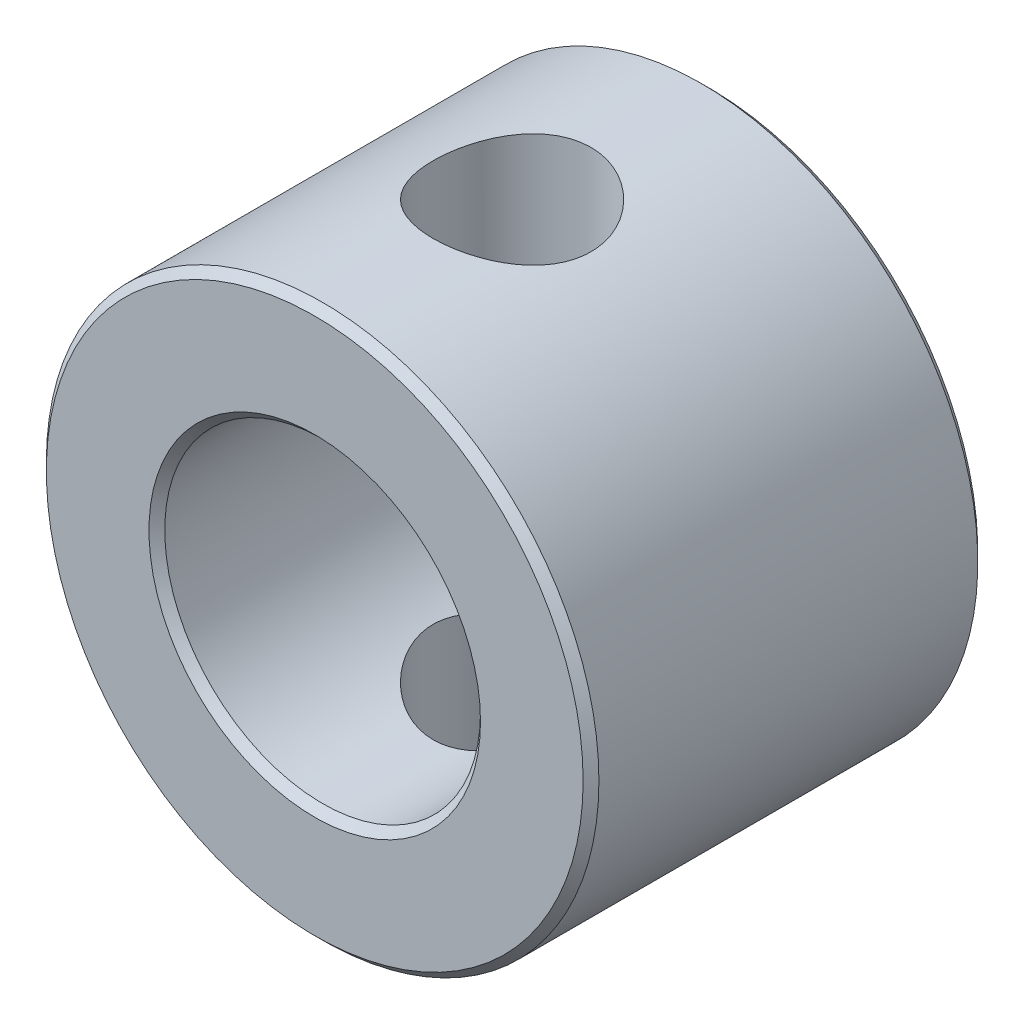
SolidWorks part; units mm, degrees
ref_plane "Front Plane" through (0, 0, 0) normal (0, 0, 1) x (1, 0, 0)
ref_plane "Top Plane" through (0, 0, 0) normal (0, 1, 0) x (1, 0, 0)
ref_plane "Right Plane" through (0, 0, 0) normal (1, 0, 0) x (0, 0, -1)
ref_plane "Plane1" through (0, 0, 0) normal (0, -1, 0) x (1, 0, 0)
sketch "Sketch1" plane through (0, 0, 0) normal (0, -1, 0) x (1, 0, 0)
  line L0 (7, 10) -> (0, 10)
  line L1 (0, 10) -> (0, 0)
  line L2 (0, 0) -> (7, 0)
  line L3 (7, 0) -> (7, 10)
  line L4 (0, 10) -> (0, 0) construction
revolve "Revolve1" add sketch "Sketch1" angle 360 about L4
hole_wizard "Ø8.0 (8) Diameter Hole1" positions "Sketch3" profile "Sketch2" hole size "Ø8.0" standard "ANSI Metric"
sketch "Sketch3" plane through (0, 0, 10) normal (0, 0, 1) x (1, 0, 0)
  point P0 (0, 0)
sketch "Sketch2" plane through (0, 0, 10) normal (1, 0, 0) x (0, -1, 0)
  line L0 (0, 0) -> (0, 10)
  line L1 (0, 10) -> (4, 10)
  line L2 (4, 10) -> (4, 0)
  line L5 (4, 0) -> (0, 0)
  line L11 (0, -6.35) -> (0, 107.95) construction
  dimension "Thru Hole Dia." = 8
  dimension "Thru Hole Depth" = 10
hole_wizard "Ø4.0 (4) Diameter Hole1" positions "3DSketch1" profile "Sketch4" hole size "Ø4.0" standard "ANSI Metric"
sketch3d "3DSketch1"
  point P0 (0, 7, 5)
sketch "Sketch4" plane through (0, 7, 5) normal (1, 0, 0) x (0, 0, 1)
  line L0 (0, 0) -> (0, 17.5359)
  line L1 (0, 17.5359) -> (2, 17.5359)
  line L2 (2, 17.5359) -> (2, 0)
  line L5 (2, 0) -> (0, 0)
  line L10 (0, 17.5359) -> (-2, 17.5359) construction
  line L11 (0, -6.35) -> (0, 107.95) construction
  dimension "Hole Dia." = 4
  dimension "Hole Depth" = 17.5359
  dimension "Drill Angle" = 180
chamfer "Chamfer1" distance 0.2 angle 45 4 edges at (-7, 0, 0) (-7, 0, 10) (4, 0, 0) (4, 0, 10)
